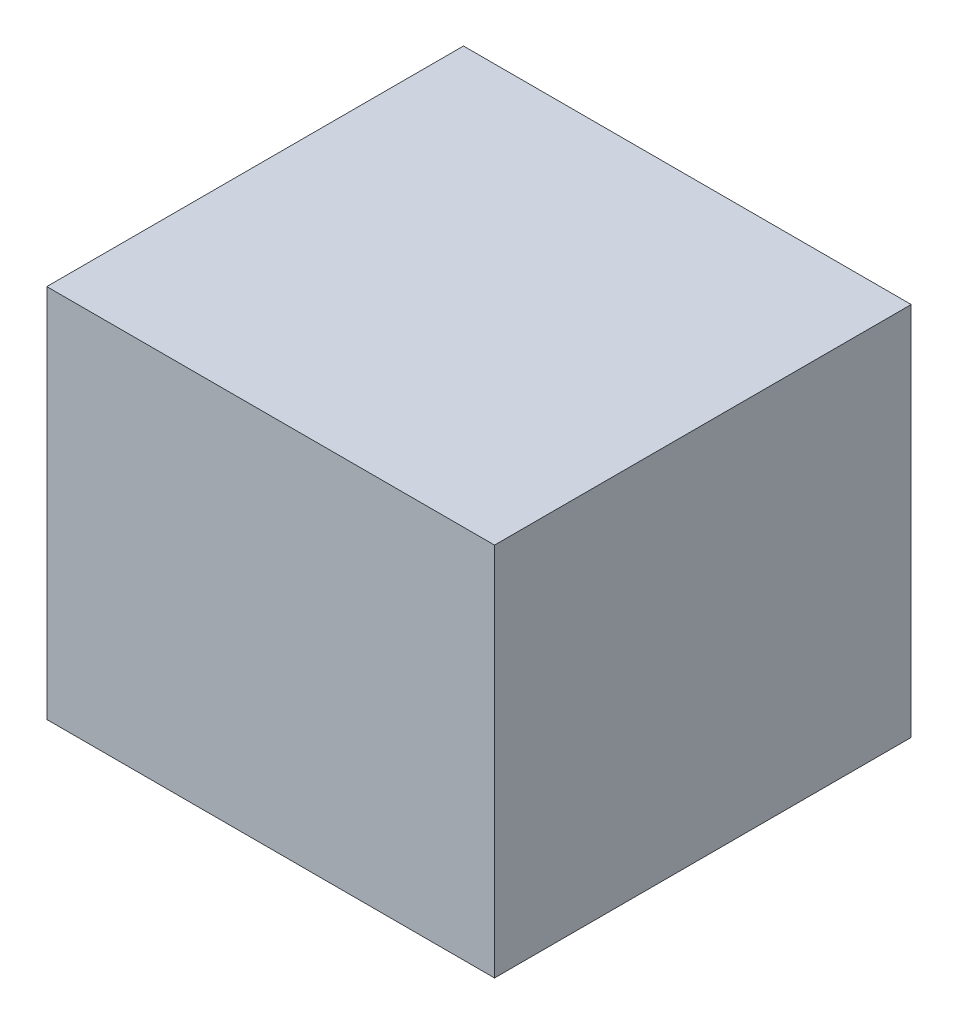
SolidWorks part; units mm, degrees
ref_plane "Front Plane" through (0, 0, 0) normal (0, 0, 1) x (1, 0, 0)
ref_plane "Top Plane" through (0, 0, 0) normal (0, 1, 0) x (1, 0, 0)
ref_plane "Right Plane" through (0, 0, 0) normal (1, 0, 0) x (0, 0, -1)
sketch "Sketch1" plane through (0, 0, 0) normal (1, 0, 0) x (0, 0, -1)
  line L1 (-19.45, -17.5) -> (19.45, -17.5)
  line L2 (-19.45, -17.5) -> (-19.45, 17.5)
  line L3 (-19.45, 17.5) -> (19.45, 17.5)
  line L4 (19.45, -17.5) -> (19.45, 17.5)
  line L5 (-19.45, -17.5) -> (19.45, 17.5) construction
  line L6 (-19.45, 17.5) -> (19.45, -17.5) construction
  point P0 (0, 0)
  dimension "D1" = 38.9
  dimension "D2" = 35
extrude "Boss-Extrude1" add sketch "Sketch1" along normal blind 41.8
